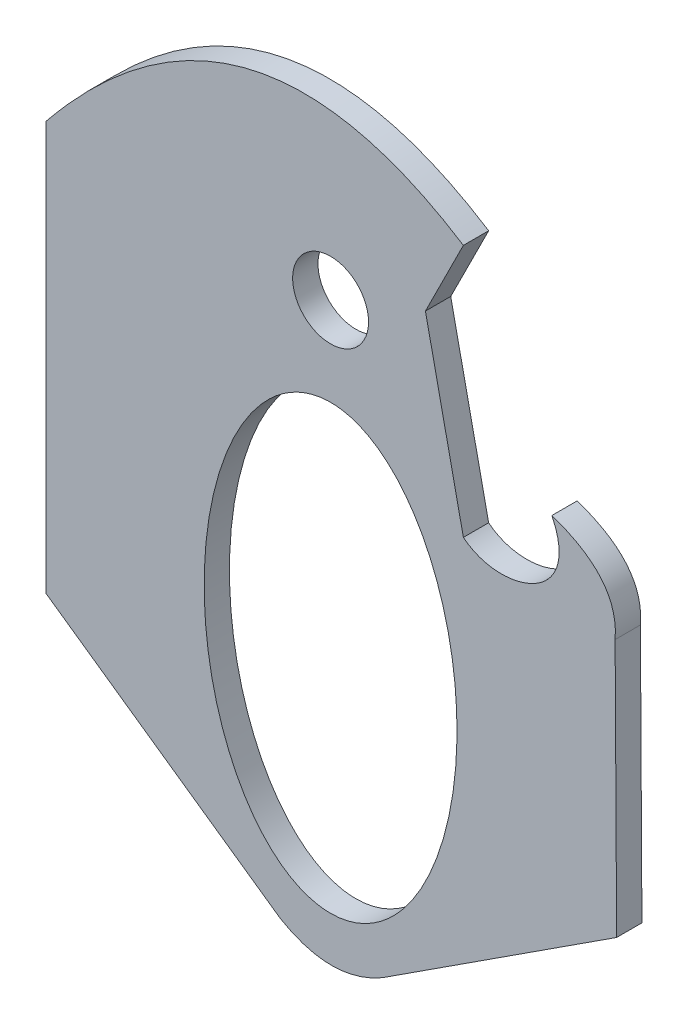
SolidWorks part; units mm, degrees
ref_plane "Front Plane" through (0, 0, 0) normal (0, 0, 1) x (1, 0, 0)
ref_plane "Top Plane" through (0, 0, 0) normal (0, 1, 0) x (1, 0, 0)
ref_plane "Right Plane" through (0, 0, 0) normal (1, 0, 0) x (0, 0, -1)
sketch "Sketch1" plane through (0, 0, 0) normal (0, 0, 1) x (1, 0, 0)
  line L0 (10.5, 37.5) -> (10.5, -37.5) construction
  line L1 (-22.5, 37.5) -> (22.5, 37.5) construction
  line L2 (-22.5, 37.5) -> (-22.5, -37.5) construction
  line L3 (-22.5, -37.5) -> (22.5, -37.5) construction
  line L4 (22.5, 37.5) -> (22.5, -37.5) construction
  line L5 (-22.5, 13.5443) -> (-22.5, 12.5) construction
  line L6 (-22.5, 12.5) -> (22.5, 12.5) construction
  line L7 (-22.5, 33.5) -> (22.5, 33.5) construction
  line L8 (-22.5, 27.5) -> (22.5, 27.5) construction
  line L9 (7.5, 37.5) -> (7.5, -37.5) construction
  line L10 (17.5, -37.5) -> (17.5, 37.5) construction
  line L11 (-22.5, -24.5) -> (22.5, -24.5) construction
  line L12 (0, 41.2703) -> (0, -43.4736) construction
  line L13 (-22.5, -36.5) -> (22.5, -36.5) construction
  line L14 (-4, -9.5001) -> (-4, -37.1292) construction
  line L15 (-22.5, 25.5) -> (22.5, 25.5) construction
  line L16 (-22.4246, -9.5001) -> (22.5, -9.5001) construction
  line L17 (10.5, 33.5) -> (7.5, 27.5)
  line L18 (7.5, 27.5) -> (10.5, 13.5)
  line L19 (22.5, 13.5) -> (-22.5, 13.5) construction
  line L20 (4.0909, -9.5001) -> (4, -37.5) construction
  line L21 (-22.5, -4.5001) -> (22.5, -4.5001) construction
  line L22 (-22.5, 18.5) -> (22.5, 18.5) construction
  line L23 (-4, -23.3147) -> (-21.0769, -11.3147) construction
  line L24 (4.0909, -23.3147) -> (22.5909, -11.3147) construction
  line L25 (-22.5, 25.5) -> (-22.5, -4.5001)
  line L26 (-3.9705, -19.8415) -> (-21.0474, -7.8415) construction
  line L27 (4.1204, -19.8415) -> (22.6204, -7.8415) construction
  line L28 (-22.5, -4.5001) -> (-22.5, -6.8458)
  line L29 (-22.5, -6.8458) -> (-3.9705, -19.8415)
  line L30 (22.5, 12.5) -> (22.6204, -7.8415)
  line L31 (22.6204, -7.8415) -> (4.1204, -19.8415)
  spline S0 degree 2 poles (-3.9705, -19.8415) (0.0678, -22.2124) (4.1204, -19.8415) knots 0 0 0 1 1 1 construction
  spline S1 degree 2 poles (-22.5, 25.5) (-6.9576, 44.6827) (10.5, 33.5) knots 0 0 0 1 1 1
  spline S2 degree 3 poles (10.5, 13.5) (13.4962, 11.0276) (20.0373, 13.3064) (17.5, 18.5) knots 0 0 0 0 1 1 1 1
  spline S3 degree 2 poles (17.5, 18.5) (22.8536, 16.682) (22.5, 12.5) knots 0 0 0 1 1 1
  spline S4 degree 2 poles (-4, -23.3147) (0.0383, -25.6856) (4.0909, -23.3147) knots 0 0 0 1 1 1 construction
  spline S5 degree 2 poles (-3.9705, -19.8415) (0.0711, -22.2124) (4.1204, -19.8415) knots 0 0 0 1 1 1
  point P0 (0, 0)
  point P18 (0, -24.5)
  point P19 (4, -37.5)
  point P24 (-5.4231, -36.5)
  point P25 (7.5, -36.5)
  point P43 (13.5, 12.5)
  point P44 (16.66, 13.5)
  dimension "D1" = 45
  dimension "D2" = 75
  dimension "D3" = 12
  dimension "D4" = 4
  dimension "D5" = 10
  dimension "D6" = 15
  dimension "D7" = 5
  dimension "D8" = 13
  dimension "D9" = 4
  dimension "D10" = 1
  dimension "D11" = 2
  dimension "D12" = 51
  dimension "D13" = 15
  dimension "D14" = 50
  dimension "D15" = 28
  dimension "D16" = 3.16
  dimension "D17" = 4
  dimension "D18" = 5
extrude "Boss-Extrude1" add sketch "Sketch1" along normal blind 2
sketch "Sketch2" plane through (0, 0, 2) normal (0, 0, 1) x (1, 0, 0)
  line L0 (17.5, 18.5) -> (-34.592, 18.5) construction
  circle A0 centre (0, 24.5) radius 3
  dimension "D1" = 6
  dimension "D2" = 6
extrude "Cut-Extrude1" cut sketch "Sketch2" against normal through all
sketch "Sketch3" plane through (0, 0, 2) normal (0, 0, 1) x (1, 0, 0)
  line L0 (0, 0) -> (0, 17.5) construction
  line L1 (0, 0) -> (0, -17.5) construction
  ellipse E0 centre (0, 0) end of major axis (0, -17.5) minor radius 10
  dimension "D1" = 17.5
  dimension "D2" = 17.5
  dimension "D3" = 10
extrude "Cut-Extrude2" cut sketch "Sketch3" against normal through all
ref_plane "Plane1" through (0, 0, 2) normal (0, 0, 1) x (1, 0, 0)
